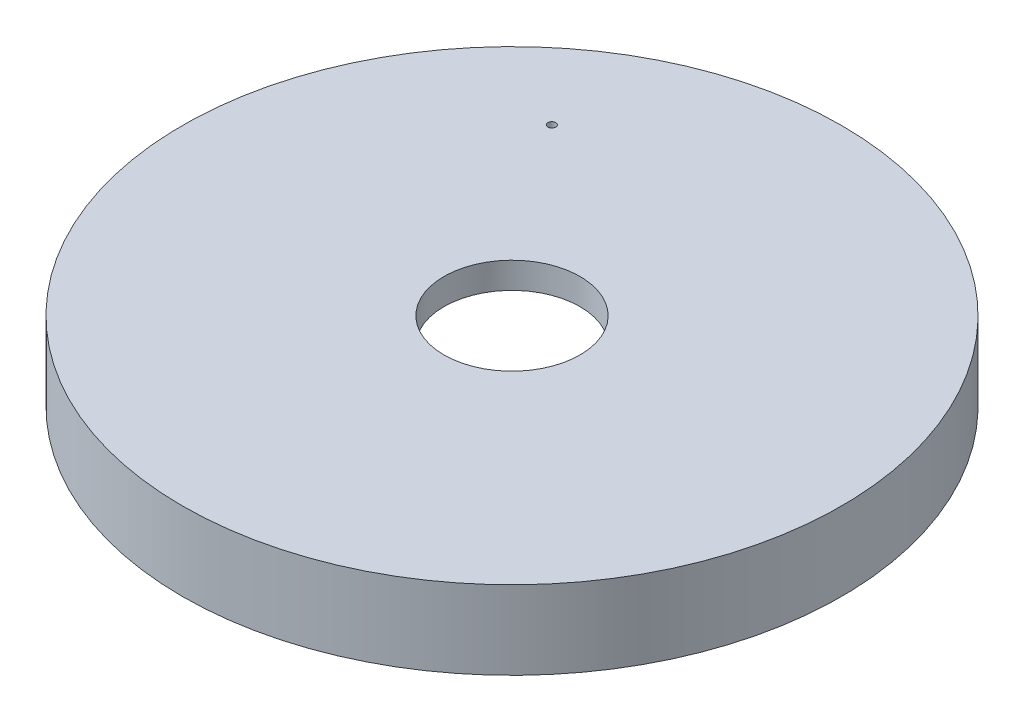
SolidWorks part; units mm, degrees
material "HYPALON"
ref_plane "Płaszczyzna przednia" through (0, 0, 0) normal (0, 0, 1) x (1, 0, 0)
ref_plane "Płaszczyzna górna" through (0, 0, 0) normal (0, 1, 0) x (1, 0, 0)
ref_plane "Płaszczyzna prawa" through (0, 0, 0) normal (1, 0, 0) x (0, 0, -1)
sketch "Szkic1" plane through (0, 0, 0) normal (0, 0, 1) x (1, 0, 0)
  line L0 (13, 2.5) -> (63, 2.5)
  line L1 (63, 2.5) -> (63, -12.5)
  line L2 (63, -12.5) -> (40.4748, -12.5)
  line L3 (40.4748, -12.5) -> (13, -2.5)
  line L4 (13, -2.5) -> (13, 2.5)
  line L5 (0, 24.6083) -> (0, -34.5814) construction
  point P8 (13, 0)
  dimension "D1" = 13
  dimension "D2" = 63
  dimension "D3" = 160
  dimension "D4" = 5
  dimension "D5" = 15
revolve "Obrót1" add sketch "Szkic1" angle 360 about L5
sketch "Szkic2" plane through (0, 0, 0) normal (0, 1, 0) x (1, 0, 0)
  line L0 (-27.786, 35.3969) -> (0, 0) construction
  line L1 (0, 0) -> (33.1748, -42.2618) construction
  circle A0 centre (-27.786, 35.3969) radius 0.75
  dimension "D1" = 45
  dimension "D2" = 1.5
extrude "Wytnij-wyciągnięcie2" cut sketch "Szkic2" against normal mid plane 30
